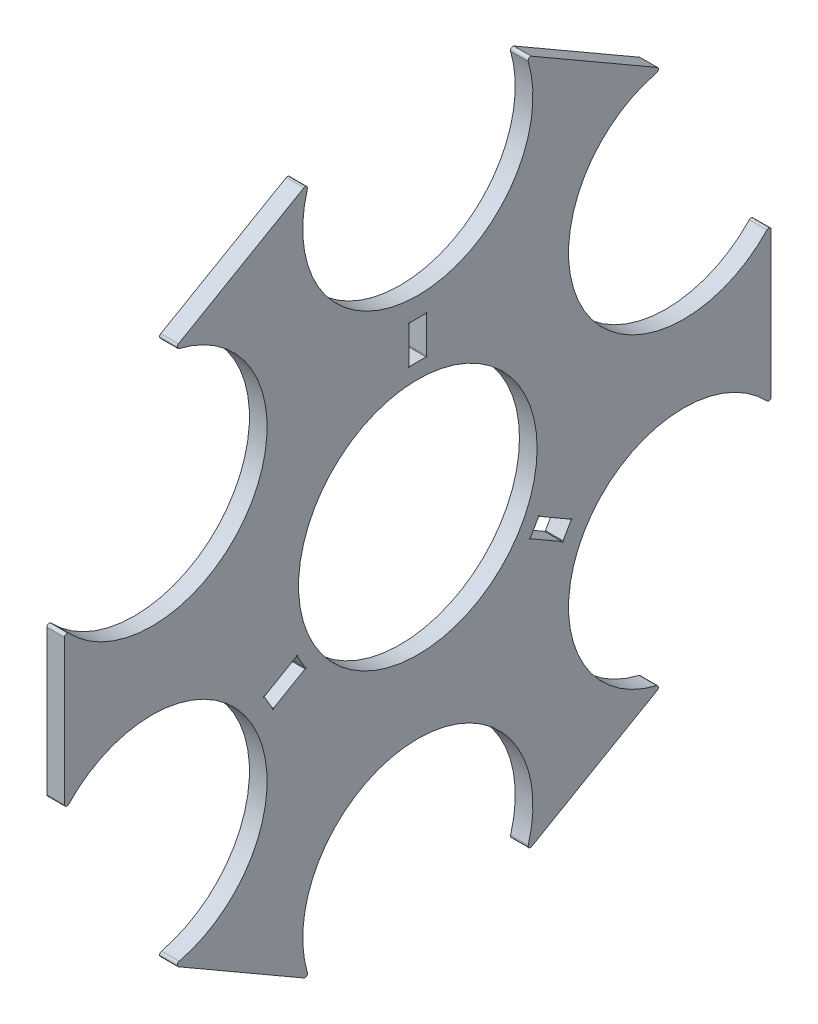
SolidWorks part; units mm, degrees
ref_plane "Front Plane" through (0, 0, 0) normal (0, 0, 1) x (1, 0, 0)
ref_plane "Top Plane" through (0, 0, 0) normal (0, 1, 0) x (1, 0, 0)
ref_plane "Right Plane" through (0, 0, 0) normal (1, 0, 0) x (0, 0, -1)
sketch "Sketch2" plane through (0, 0, 0) normal (1, 0, 0) x (0, 0, -1)
  line L0 (35.921, 114.3) -> (-35.921, 114.3) construction
  line L1 (81.0262, 88.2585) -> (35.921, 114.3)
  line L2 (116.9472, -26.0415) -> (116.9472, 26.0415)
  line L3 (35.921, -114.3) -> (81.0262, -88.2585)
  line L4 (-81.0262, -88.2585) -> (-35.921, -114.3)
  line L5 (-116.9472, 26.0415) -> (-116.9472, -26.0415)
  line L6 (-35.921, 114.3) -> (-81.0262, 88.2585)
  circle A0 centre (0, 0) radius 101.6 construction
  arc A1 (-35.921, 114.3) -> (35.921, 114.3) centre (0, 101.6) ccw
  arc A2 (81.0262, 88.2585) -> (116.9472, 26.0415) centre (87.9882, 50.8) ccw
  arc A3 (116.9472, -26.0415) -> (81.0262, -88.2585) centre (87.9882, -50.8) ccw
  arc A4 (35.921, -114.3) -> (-35.921, -114.3) centre (0, -101.6) ccw
  arc A5 (-81.0262, -88.2585) -> (-116.9472, -26.0415) centre (-87.9882, -50.8) ccw
  arc A6 (-116.9472, 26.0415) -> (-81.0262, 88.2585) centre (-87.9882, 50.8) ccw
  circle A7 centre (0, 0) radius 39.4875
  point P23 (0, 0)
  point P34 (0, 0)
  dimension "D1" = 203.2
  dimension "D2" = 114.3
  dimension "D3" = 76.2
  dimension "D6" = 78.9749
  dimension "D4" = 6
  dimension "D5" = 6
extrude "Boss-Extrude1" add sketch "Sketch2" along normal blind 5.842
fillet "Fillet1" radius 0.7937 12 edges at (2.921, -114.3, 35.921) (2.921, -114.3, -35.921) (2.921, -88.2585, -81.0262) (2.921, -26.0415, -116.9472) (2.921, 88.2585, -81.0262) (2.921, 26.0415, -116.9472) (2.921, -88.2585, 81.0262) (2.921, -26.0415, 116.9472) (2.921, 26.0415, 116.9472) (2.921, 88.2585, 81.0262) (2.921, 114.3, -35.921) (2.921, 114.3, 35.921)
sketch "Sketch3" plane through (5.842, 0, 0) normal (1, 0, 0) x (0, 0, -1)
  line L0 (0, 0) -> (0, 50.8) construction
  line L2 (6.1516, 53.721) -> (-6.1516, 53.721)
  line L3 (6.35, 53.5226) -> (6.35, 48.0774)
  line L4 (6.1516, 47.879) -> (-6.1516, 47.879)
  line L5 (-6.35, 53.5226) -> (-6.35, 48.0774)
  line L6 (6.35, 53.721) -> (-6.35, 47.879) construction
  line L7 (6.35, 47.879) -> (-6.35, 53.721) construction
  arc A0 (-6.1516, 53.721) -> (-6.35, 53.5226) centre (-6.35, 53.721) ccw
  arc A1 (-6.35, 48.0774) -> (-6.1516, 47.879) centre (-6.35, 47.879) ccw
  arc A2 (6.1516, 47.879) -> (6.35, 48.0774) centre (6.35, 47.879) ccw
  arc A3 (6.35, 53.5226) -> (6.1516, 53.721) centre (6.35, 53.721) ccw
  dimension "D4" = 0.3969
  dimension "D5" = 0.3969
  dimension "D6" = 0.3969
  dimension "D7" = 0.3969
  dimension "D1" = 50.8
  dimension "D2" = 12.7
  dimension "D3" = 5.842
extrude "Cut-Extrude2" [suppressed] cut sketch "Sketch3" against normal through all
pattern_circular "CirPattern1" [suppressed] count 3 every 120
sketch "Sketch4" plane through (5.842, 0, 0) normal (1, 0, 0) x (0, 0, -1)
  line L0 (47.9712, -31.0114) -> (50.8422, -26.0386)
  line L1 (2.871, 57.05) -> (-2.871, 57.05)
  line L2 (2.871, 57.05) -> (2.871, 44.55)
  line L3 (2.871, 44.55) -> (-2.871, 44.55)
  line L4 (-2.871, 57.05) -> (-2.871, 44.55)
  line L5 (2.871, 57.05) -> (-2.871, 44.55) construction
  line L6 (2.871, 44.55) -> (-2.871, 57.05) construction
  line L7 (47.9712, -31.0114) -> (37.1459, -24.7614)
  line L8 (37.1459, -24.7614) -> (40.0169, -19.7886)
  line L9 (50.8422, -26.0386) -> (40.0169, -19.7886)
  line L10 (47.9712, -31.0114) -> (40.0169, -19.7886) construction
  line L11 (37.1459, -24.7614) -> (50.8422, -26.0386) construction
  line L12 (-50.8422, -26.0386) -> (-47.9712, -31.0114)
  line L13 (-50.8422, -26.0386) -> (-40.0169, -19.7886)
  line L14 (-40.0169, -19.7886) -> (-37.1459, -24.7614)
  line L15 (-47.9712, -31.0114) -> (-37.1459, -24.7614)
  line L16 (-50.8422, -26.0386) -> (-37.1459, -24.7614) construction
  line L17 (-40.0169, -19.7886) -> (-47.9712, -31.0114) construction
  circle A0 centre (0, 0) radius 50.8 construction
  point P3 (0, 50.8)
  point P10 (43.9941, -25.4)
  point P15 (-43.9941, -25.4)
  point P20 (0, 0)
  dimension "D1" = 101.6
  dimension "D2" = 12.5
  dimension "D3" = 5.742
  dimension "D4" = 3
extrude "Cut-Extrude3" cut sketch "Sketch4" against normal through all
sketch "Sketch5" plane through (5.842, 0, 0) normal (1, 0, 0) x (0, 0, -1)
  line L0 (-2.871, 50.8) -> (2.871, 50.8) construction
  line L1 (-2.871, 57.05) -> (-2.871, 44.55) construction
  line L2 (2.871, 44.55) -> (2.871, 57.05) construction
  line L3 (45.4296, -22.9136) -> (42.5586, -27.8864) construction
  line L4 (-42.5586, -27.8864) -> (-45.4296, -22.9136) construction
  circle A0 centre (2.871, 57.05) radius 0.1984
  circle A1 centre (-2.871, 57.05) radius 0.1984
  circle A2 centre (-2.871, 44.55) radius 0.1984
  circle A3 centre (2.871, 44.55) radius 0.1984
  circle A4 centre (47.9712, -31.0114) radius 0.1984
  circle A5 centre (50.8422, -26.0386) radius 0.1984
  circle A6 centre (40.0169, -19.7886) radius 0.1984
  circle A7 centre (37.1459, -24.7614) radius 0.1984
  circle A8 centre (-50.8422, -26.0386) radius 0.1984
  circle A9 centre (-47.9712, -31.0114) radius 0.1984
  circle A10 centre (-37.1459, -24.7614) radius 0.1984
  circle A11 centre (-40.0169, -19.7886) radius 0.1984
  point P38 (0, 0)
  dimension "D1" = 0.3969
  dimension "D2" = 0.3969
  dimension "D3" = 3
extrude "Cut-Extrude4" cut sketch "Sketch5" against normal through all
